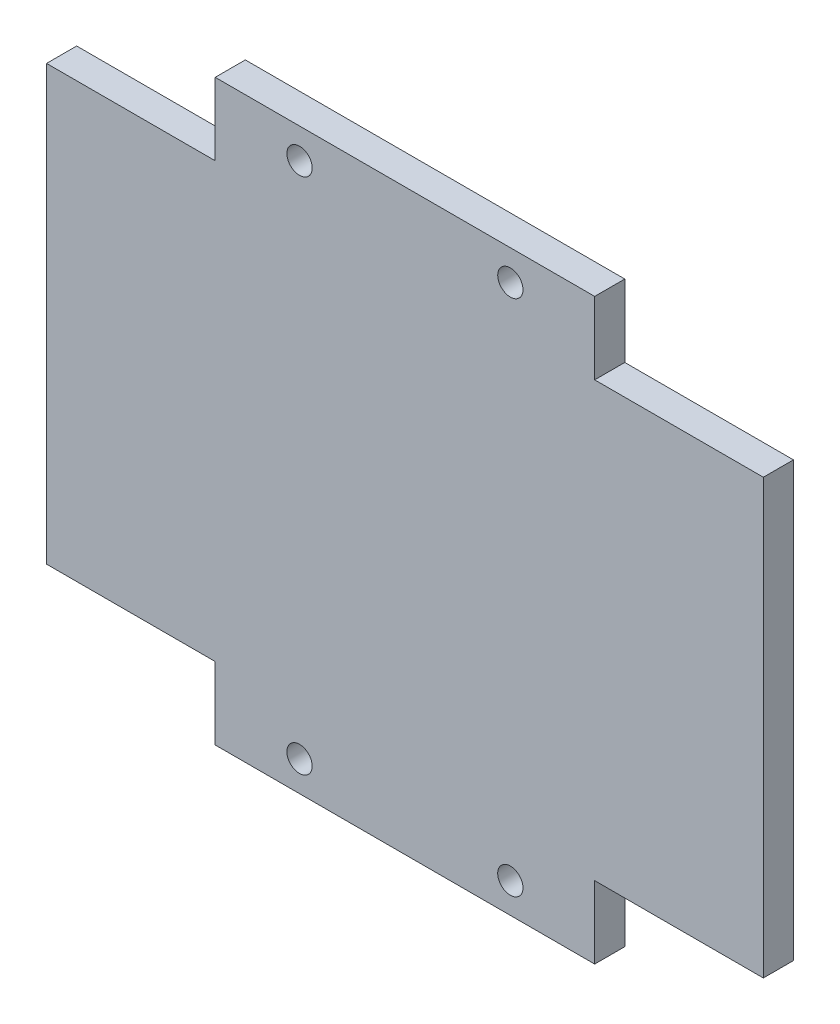
SolidWorks part; units mm, degrees
ref_plane "Front Plane" through (0, 0, 0) normal (0, 0, 1) x (1, 0, 0)
ref_plane "Top Plane" through (0, 0, 0) normal (0, 1, 0) x (1, 0, 0)
ref_plane "Right Plane" through (0, 0, 0) normal (1, 0, 0) x (0, 0, -1)
sketch "Sketch2" plane through (0, 0, 0) normal (0, 0, 1) x (1, 0, 0)
  line L1 (0, 0) -> (63, 0)
  line L2 (0, 0) -> (0, 96)
  line L3 (0, 96) -> (63, 96)
  line L4 (63, 0) -> (63, 96)
  dimension "D1" = 96
  dimension "D2" = 63
extrude "Boss-Extrude1" add sketch "Sketch2" along normal blind 5
sketch "Sketch3" plane through (0, 0, 5) normal (0, 0, 1) x (1, 0, 0)
  line L0 (63, 96) -> (0, 96) construction
  line L1 (0, 96) -> (0, 0) construction
  line L2 (31.5, 66.7376) -> (31.5, 29.4197) construction
  line L3 (19.4472, 48) -> (50.0643, 48) construction
  line L4 (63, 0) -> (63, 96) construction
  circle A0 centre (14, 91) radius 2.1
  circle A2 centre (49, 91) radius 2.1
  circle A3 centre (49, 5) radius 2.1
  circle A4 centre (14, 5) radius 2.1
  dimension "D1" = 4.2
  dimension "D2" = 5
  dimension "D3" = 14
  dimension "D4" = 48
  dimension "D5" = 31.5
extrude "Cut-Extrude1" cut sketch "Sketch3" against normal blind 5
sketch "Sketch4" plane through (0, 0, 5) normal (0, 0, 1) x (1, 0, 0)
  line L0 (63, 0) -> (63, 96) construction
  line L1 (63, 84) -> (91, 84)
  line L2 (63, 84) -> (63, 12)
  line L3 (63, 12) -> (91, 12)
  line L4 (91, 84) -> (91, 12)
  line L5 (0, 96) -> (0, 0) construction
  line L6 (0, 84) -> (-28, 84)
  line L7 (0, 84) -> (0, 12)
  line L8 (0, 12) -> (-28, 12)
  line L9 (-28, 84) -> (-28, 12)
  line L10 (63, 96) -> (0, 96) construction
  line L11 (0, 0) -> (63, 0) construction
  dimension "D1" = 12
  dimension "D2" = 12
  dimension "D3" = 28
  dimension "D4" = 28
  dimension "D5" = 12
  dimension "D6" = 12
extrude "Boss-Extrude2" add sketch "Sketch4" against normal blind 5
